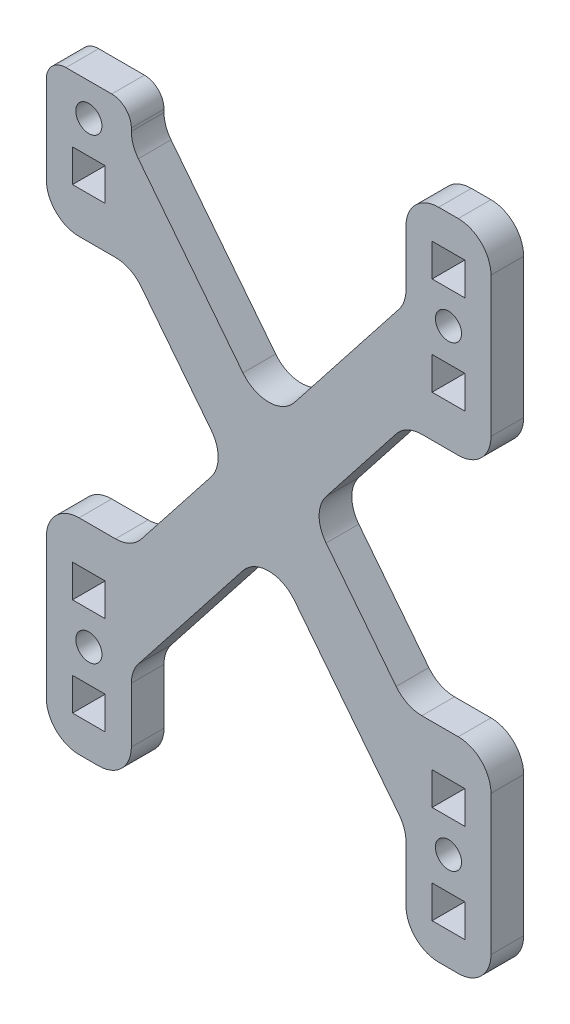
SolidWorks part; units mm, degrees
ref_plane "Plan de face" through (0, 0, 0) normal (0, 0, 1) x (1, 0, 0)
ref_plane "Plan de dessus" through (0, 0, 0) normal (0, 1, 0) x (1, 0, 0)
ref_plane "Plan de droite" through (0, 0, 0) normal (1, 0, 0) x (0, 0, -1)
sketch "Esquisse1" plane through (0, 0, 0) normal (0, 0, 1) x (1, 0, 0)
  line L0 (0, 0) -> (0, 50.4359) construction
  line L1 (-34.2034, 0) -> (29.4797, 0) construction
  line L2 (34, 50) -> (34, 18.6343)
  line L3 (34, 18.6343) -> (21, 18.6343)
  line L4 (21, 18.6343) -> (6.3587, 0)
  line L5 (34, 50) -> (21, 50)
  line L6 (21, 50) -> (21, 34.8202)
  line L7 (21, 34.8202) -> (0, 8.093)
  line L8 (27.5, 35) -> (0, 0) construction
  line L9 (21, -18.6343) -> (6.3587, 0)
  line L10 (34, -18.6343) -> (21, -18.6343)
  line L11 (34, -50) -> (34, -18.6343)
  line L12 (34, -50) -> (21, -50)
  line L13 (21, -50) -> (21, -34.8202)
  line L14 (21, -34.8202) -> (0, -8.093)
  line L15 (-21, 34.8202) -> (0, 8.093)
  line L16 (-21, 50) -> (-21, 34.8202)
  line L17 (-34, 50) -> (-21, 50)
  line L18 (-34, 50) -> (-34, 18.6343)
  line L19 (-34, 18.6343) -> (-21, 18.6343)
  line L20 (-21, 18.6343) -> (-6.3587, 0)
  line L21 (-21, -18.6343) -> (-6.3587, 0)
  line L22 (-34, -18.6343) -> (-21, -18.6343)
  line L23 (-34, -50) -> (-34, -18.6343)
  line L24 (-34, -50) -> (-21, -50)
  line L25 (-21, -50) -> (-21, -34.8202)
  line L26 (-21, -34.8202) -> (0, -8.093)
  line B0 (27.5, 30) -> (27.5, 40) construction
  line B1 (25, 30) -> (25, 25)
  line B2 (25, 30) -> (30, 30)
  line B3 (30, 30) -> (30, 25)
  line B4 (25, 25) -> (30, 25)
  line B5 (25, 40) -> (25, 45)
  line B6 (25, 40) -> (30, 40)
  line B7 (30, 40) -> (30, 45)
  line B8 (25, 45) -> (30, 45)
  circle B9 centre (27.5, 35) radius 2
  line B10 (-25, 30) -> (-25, 25)
  line B11 (-25, 30) -> (-30, 30)
  line B12 (-30, 30) -> (-30, 25)
  line B13 (-25, 25) -> (-30, 25)
  line B14 (-25, 40) -> (-25, 45)
  line B15 (-25, 40) -> (-30, 40)
  line B16 (-30, 40) -> (-30, 45)
  line B17 (-25, 45) -> (-30, 45)
  circle B18 centre (-27.5, 35) radius 2
  line B19 (-25, -30) -> (-25, -25)
  line B20 (-25, -30) -> (-30, -30)
  line B21 (-30, -30) -> (-30, -25)
  line B22 (-25, -25) -> (-30, -25)
  line B23 (-25, -40) -> (-25, -45)
  line B24 (-25, -40) -> (-30, -40)
  line B25 (-30, -40) -> (-30, -45)
  line B26 (-25, -45) -> (-30, -45)
  circle B27 centre (-27.5, -35) radius 2
  line B28 (25, -30) -> (25, -25)
  line B29 (25, -30) -> (30, -30)
  line B30 (30, -30) -> (30, -25)
  line B31 (25, -25) -> (30, -25)
  line B32 (25, -40) -> (25, -45)
  line B33 (25, -40) -> (30, -40)
  line B34 (30, -40) -> (30, -45)
  line B35 (25, -45) -> (30, -45)
  circle B36 centre (27.5, -35) radius 2
  dimension "D1" = 70
  dimension "D2" = 50
  dimension "D3" = 5
  dimension "D4" = 5
  dimension "D5" = 5
  dimension "D6" = 4
  dimension "D7" = 4
sketch_block_instance "Trou M4 plots 5mm-1"
sketch_block "Trou M4 plots 5mm" parameters "D2"=4, "D1"=5, "D3"=5, "D4"=10
sketch_block_instance "Trou M4 plots 5mm-3"
sketch_block_instance "Trou M4 plots 5mm-4"
sketch_block_instance "Trou M4 plots 5mm-5"
extrude "Boss.-Extru.1" add sketch "Esquisse1" along normal blind 5
fillet "Congé1" radius 5 24 edges at (21, -34.8202, 2.5) (21, -50, 2.5) (34, -50, 2.5) (34, -18.6343, 2.5) (21, -18.6343, 2.5) (-21, -34.8202, 2.5) (-21, -50, 2.5) (-34, -50, 2.5) (-34, -18.6343, 2.5) (-21, -18.6343, 2.5) (0, -8.093, 2.5) (-6.3587, 0, 2.5) (6.3587, 0, 2.5) (0, 8.093, 2.5) (-21, 18.6343, 2.5) (-34, 18.6343, 2.5) (-34, 50, 2.5) (-21, 34.8202, 2.5) (-21, 50, 2.5) (34, 18.6343, 2.5) (21, 18.6343, 2.5) (21, 34.8202, 2.5) (21, 50, 2.5) (34, 50, 2.5)
sketch "Esquisse2" plane through (0, 0, 5) normal (0, 0, 1) x (1, 0, 0)
  line L0 (-34, 45) -> (-34, 23.6343) construction
  line L1 (-34, 40) -> (-21, 40)
  line L2 (-34, 40) -> (-34, 50)
  line L3 (-34, 50) -> (-21, 50)
  line L4 (-21, 40) -> (-21, 50)
  line L5 (-26, 50) -> (-29, 50) construction
  line L6 (-30, 40) -> (-25, 40) construction
  line L7 (-21, 36.5495) -> (-21, 45) construction
extrude "Enlèv. mat.-Extru.1" cut sketch "Esquisse2" against normal through all
fillet "Congé2" radius 3 2 edges at (-34, 40, 2.5) (-21, 40, 2.5)
